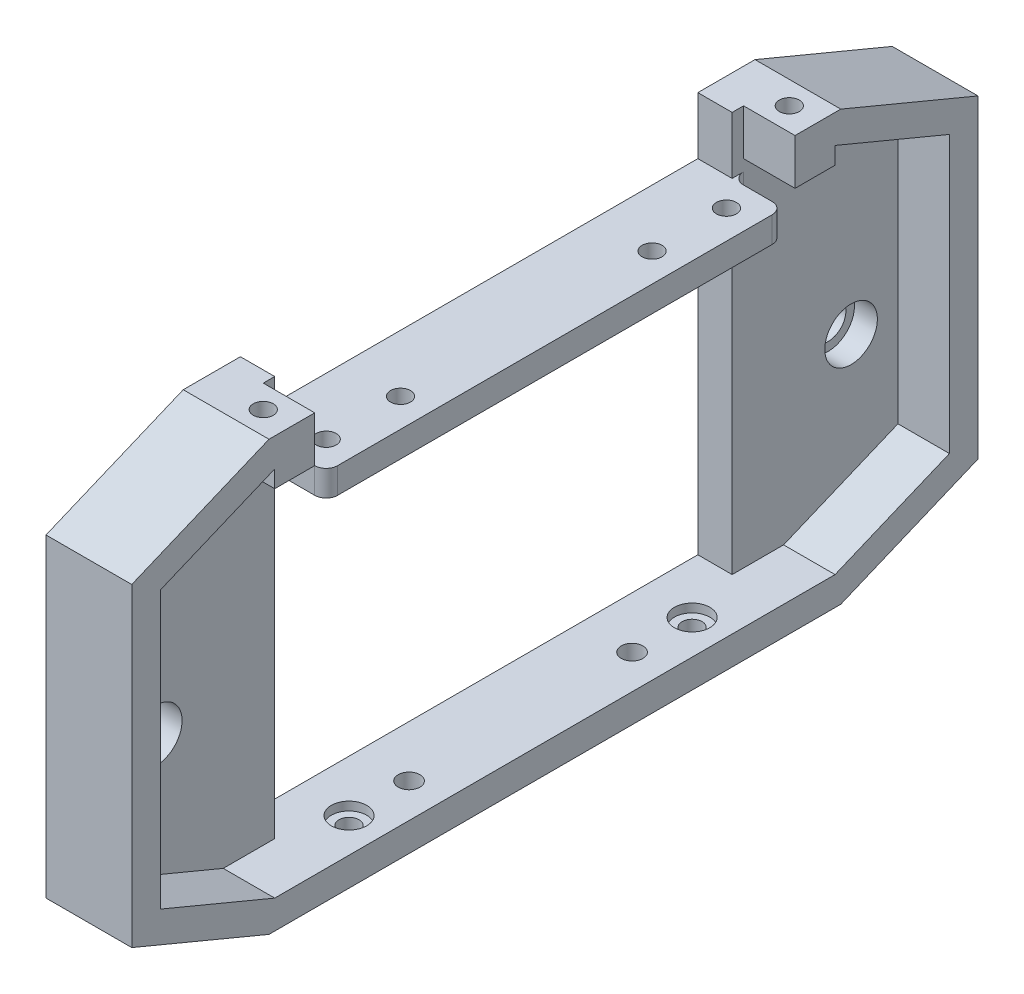
SolidWorks part; units mm, degrees
ref_plane "Front Plane" through (0, 0, 0) normal (0, 0, 1) x (1, 0, 0)
ref_plane "Top Plane" through (0, 0, 0) normal (0, 1, 0) x (1, 0, 0)
ref_plane "Right Plane" through (0, 0, 0) normal (1, 0, 0) x (0, 0, -1)
sketch "Sketch13" plane through (0, 0, 0) normal (1, 0, 0) x (0, 0, -1)
  line L0 (0, 0) -> (-24, 10)
  line L1 (0, 0) -> (100, 0)
  line L3 (0, 75) -> (10, 75)
  line L5 (-24, 10) -> (-24, 65)
  line L6 (-24, 65) -> (0, 75)
  line L7 (100, 75) -> (124, 65)
  line L8 (124, 65) -> (124, 10)
  line L9 (124, 10) -> (100, 0)
  line L10 (-10.8, 31) -> (110.8, 31) construction
  line L11 (10, 60) -> (90, 60)
  line L12 (10, 60) -> (10, 5)
  line L13 (10, 5) -> (90, 5)
  line L14 (90, 60) -> (90, 5)
  line L16 (10, 75) -> (10, 65)
  line L17 (10, 65) -> (90, 65)
  line L18 (90, 65) -> (90, 75)
  line L19 (90, 75) -> (100, 75)
  circle A0 centre (-10.8, 31) radius 4.6
  circle A1 centre (110.8, 31) radius 4.6
  dimension "D10" = 9.2
  dimension "D1" = 24
  dimension "D2" = 10
  dimension "D3" = 10
  dimension "D4" = 10
  dimension "D5" = 34
  dimension "D6" = 80
  dimension "D7" = 5
  dimension "D8" = 31
  dimension "D9" = 20.8
  dimension "D11" = 5
  dimension "D12" = 75
extrude "Boss-Extrude4" add sketch "Sketch13" along normal blind 15
sketch "Sketch14" plane through (15, 0, 0) normal (1, 0, 0) x (0, 0, -1)
  line L0 (10, 70.5) -> (10, 60.5)
  line L1 (10, 60.5) -> (90, 60.5)
  line L6 (10, 65) -> (10, 75) construction
  line L7 (99, 70) -> (92, 70)
  line L9 (90, 70.5) -> (90, 60.5)
  line L10 (8, 70) -> (8, 75)
  line L11 (10, 75) -> (0, 75) construction
  line L12 (8, 75) -> (10, 75)
  line L13 (10, 75) -> (10, 70.5)
  line L14 (90, 75) -> (90, 65) construction
  line L15 (92, 70) -> (92, 75)
  line L16 (100, 75) -> (90, 75) construction
  line L17 (92, 75) -> (90, 75)
  line L18 (90, 75) -> (90, 70.5)
  line L52 (119, 61.6667) -> (98.0769, 70.3846)
  line L53 (119, 13.3333) -> (119, 61.6667)
  line L54 (99, 5) -> (119, 13.3333)
  line L55 (1, 5) -> (99, 5)
  line L56 (-19, 13.3333) -> (1, 5)
  line L57 (-19, 61.6667) -> (-19, 13.3333)
  line L58 (10, 70) -> (1, 70)
  line L59 (1, 70) -> (-19, 61.6667)
  line L60 (119, 61.6667) -> (99, 70)
  line L61 (119, 13.3333) -> (119, 61.6667)
  line L62 (99, 5) -> (119, 13.3333)
  line L63 (1, 5) -> (99, 5)
  line L64 (-19, 13.3333) -> (1, 5)
  line L65 (-19, 61.6667) -> (-19, 13.3333)
  line L66 (8, 70) -> (1, 70)
  line L67 (1, 70) -> (-19, 61.6667)
  dimension "D2" = 2
  dimension "D3" = 2
  dimension "D1" = 5
extrude "Cut-Extrude1" cut sketch "Sketch14" against normal offset from surface (9 mm away) 6 up to face at (0, 31, 6.2)
sketch "Sketch16" plane through (0, 75, 0) normal (0, 1, 0) x (1, 0, 0)
  line L0 (10, 100) -> (10, 0) construction
  line L1 (15, 100) -> (0, 100) construction
  line L2 (15, 0) -> (0, 0) construction
  line L3 (6, 90) -> (0, 90) construction
  line L4 (6, 10) -> (0, 10) construction
  line L5 (15, 8) -> (15, 0) construction
  circle A0 centre (10, 4) radius 1.75
  circle A1 centre (10, 96) radius 1.75
  dimension "D4" = 3.5
  dimension "D1" = 6
  dimension "D2" = 6
  dimension "D3" = 5
extrude "Cut-Extrude2" cut sketch "Sketch16" against normal blind 6 and the other way through all
fillet "Fillet1" radius 2 4 edges at (15, 62.75, -90) (15, 62.75, -10) (6, 62.75, -90) (6, 62.75, -10)
sketch "Sketch17" plane through (0, 65, 0) normal (0, 1, 0) x (1, 0, 0)
  line L0 (10, 85) -> (10, 15) construction
  line L1 (6, 90) -> (0, 90) construction
  line L2 (6, 10) -> (0, 10) construction
  line L4 (15, 88) -> (15, 12) construction
  circle A0 centre (10, 15) radius 1.75
  circle A1 centre (10, 85) radius 1.75
  circle A2 centre (10, 72) radius 1.75
  circle A3 centre (10, 28) radius 1.75
  dimension "D1" = 3.5
  dimension "D2" = 5
  dimension "D3" = 5
  dimension "D4" = 13
  dimension "D5" = 13
  dimension "D6" = 5
extrude "Cut-Extrude3" cut sketch "Sketch17" against normal blind 10
sketch "Sketch18" plane through (0, 0, 0) normal (0, -1, 0) x (1, 0, 0)
  line L0 (9, -20) -> (9, -80) construction
  line L1 (0, 0) -> (0, -100) construction
  line L2 (15, 0) -> (15, -100) construction
  line L3 (9, -30.5) -> (9, -69.5) construction
  circle A0 centre (9, -20) radius 1.75
  circle A1 centre (9, -80) radius 1.75
  circle A2 centre (9, -30.5) radius 1.9
  circle A3 centre (9, -69.5) radius 1.9
  point P6 (0, -50)
  point P7 (9, -50)
  dimension "D2" = 3.5
  dimension "D4" = 3.8
  dimension "D1" = 60
  dimension "D3" = 6
  dimension "D5" = 0
  dimension "D6" = 39
  dimension "D7" = 19.5
extrude "Cut-Extrude4" cut sketch "Sketch18" against normal blind 10
sketch "Sketch21" plane through (0, 0, 0) normal (-1, 0, 0) x (0, 0, 1)
  circle A0 centre (-110.8, 31) radius 3.1
  circle A1 centre (10.8, 31) radius 3.1
  circle A2 centre (-110.8, 31) radius 4.6 construction
  circle A3 centre (10.8, 31) radius 4.6 construction
  circle A4 centre (-110.8, 31) radius 4.6
  circle A5 centre (10.8, 31) radius 4.6
  dimension "D1" = 1.5
  dimension "D2" = 1.5
extrude "Boss-Extrude7" add sketch "Sketch21" against normal blind 2
sketch "Sketch20" plane through (0, 0, 0) normal (-1, 0, 0) x (0, 0, 1)
  circle A0 centre (24, 65) radius 5.5
  circle A1 centre (-10, 75) radius 5.5
  circle A2 centre (-90, 75) radius 5.5
  circle A3 centre (-124, 65) radius 5.5
  circle A4 centre (-124, 10) radius 5.5
  circle A5 centre (-100, 0) radius 5.5
  circle A6 centre (0, 0) radius 5.5
  circle A7 centre (24, 10) radius 5.5
  dimension "D1" = 11
extrude "Boss-Extrude6" [suppressed] add sketch "Sketch20" against normal blind 0.1
sketch "Sketch22" plane through (0, 5, 0) normal (0, 1, 0) x (1, 0, 0)
  circle A0 centre (9, 20) radius 3.1
  circle A1 centre (9, 80) radius 3.1
  dimension "D1" = 6.2
extrude "Cut-Extrude5" cut sketch "Sketch22" against normal blind 1.5
sketch "Sketch23" plane through (0, 70, 0) normal (0, -1, 0) x (1, 0, 0)
  line L0 (6, -99) -> (15, -99) construction
  line L1 (15, -99) -> (15, -92) construction
  line L2 (15, -92) -> (6, -92) construction
  line L3 (6, -92) -> (6, -99) construction
  line L4 (6, -8) -> (15, -8) construction
  line L5 (15, -8) -> (15, -1) construction
  line L6 (15, -1) -> (6, -1) construction
  line L7 (6, -1) -> (6, -8) construction
  line L8 (6, -99) -> (15, -99)
  line L9 (15, -99) -> (15, -92)
  line L10 (15, -92) -> (6, -92)
  line L11 (6, -92) -> (6, -99)
  line L12 (6, -8) -> (15, -8)
  line L13 (15, -8) -> (15, -1)
  line L14 (15, -1) -> (6, -1)
  line L15 (6, -1) -> (6, -8)
  circle A0 centre (10, -96) radius 1.75 construction
  circle A1 centre (10, -4) radius 1.75 construction
  circle A2 centre (10, -96) radius 1.75
  circle A3 centre (10, -4) radius 1.75
extrude "Boss-Extrude8" add sketch "Sketch23" along normal blind 3
